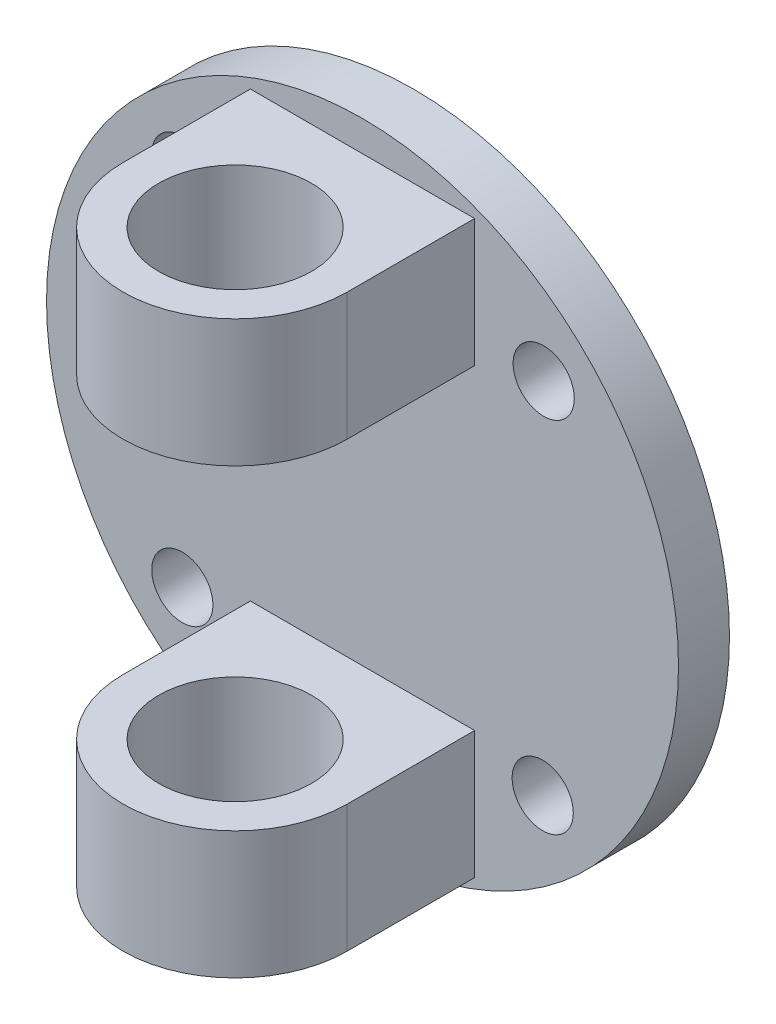
SolidWorks part; units mm, degrees
ref_plane "Front Plane" through (0, 0, 0) normal (0, 0, 1) x (1, 0, 0)
ref_plane "Top Plane" through (0, 0, 0) normal (0, 1, 0) x (1, 0, 0)
ref_plane "Right Plane" through (0, 0, 0) normal (1, 0, 0) x (0, 0, -1)
sketch "Sketch1" plane through (0, 0, 0) normal (0, 0, 1) x (1, 0, 0)
  circle A0 centre (0, 0) radius 62
  dimension "D1" = 124
extrude "Boss-Extrude1" add sketch "Sketch1" along normal blind 10 contours A0
sketch "Sketch2" plane through (0, 0, 10) normal (0, 0, 1) x (1, 0, 0)
  circle A2 centre (35.3553, -35.3553) radius 6
  circle A3 centre (-35.3553, -35.3553) radius 6
  circle A4 centre (-35.3553, 35.3553) radius 6
  circle A5 centre (35.5489, 35.1607) radius 6
  dimension "D1" = 12
  dimension "D2" = 12
  dimension "D3" = 12
  dimension "D4" = 12
extrude "Cut-Extrude1" cut sketch "Sketch2" against normal blind 10
sketch "Sketch4" plane through (0, 0, 10) normal (0, 0, 1) x (1, 0, 0)
  line L4 (-22, 31) -> (-22, 56)
  line L7 (22, 31) -> (22, 56)
  line L8 (22, 56) -> (-22, 56)
  line L10 (22, -31) -> (-22, -31)
  line L11 (-22, -31) -> (-22, -56)
  line L12 (-22, -56) -> (22, -56)
  line L13 (22, -56) -> (22, -31)
  line L14 (-22, 31) -> (22, 31)
  dimension "D1" = 25
  dimension "D2" = 25
  dimension "D4" = 25
  dimension "D5" = 44
extrude "Boss-Extrude2" add sketch "Sketch4" along normal blind 25
sketch "Sketch5" plane through (0, 56, 0) normal (0, 1, 0) x (1, 0, 0)
  line L0 (22, -35) -> (-22, -35) construction
  line L1 (-22, -35) -> (22, -35)
  arc A0 (-22, -35) -> (22, -35) centre (0, -35) ccw
  dimension "D1" = 44
extrude "Boss-Extrude5" add sketch "Sketch5" against normal blind 25 contours A0 L1
sketch "Sketch8" plane through (0, -56, 0) normal (0, -1, 0) x (1, 0, 0)
  line L0 (-22, 35) -> (22, 35) construction
  line L1 (-22, 35) -> (22, 35)
  arc A0 (22, 35) -> (-22, 35) centre (0, 35) ccw
extrude "Boss-Extrude6" add sketch "Sketch8" against normal blind 25
sketch "Sketch9" plane through (0, 56, 0) normal (0, 1, 0) x (1, 0, 0)
  circle A1 centre (0, -35) radius 15
  dimension "D1" = 30
extrude "Cut-Extrude2" cut sketch "Sketch9" against normal blind 25
sketch "Sketch10" plane through (0, -56, 0) normal (0, -1, 0) x (1, 0, 0)
  circle A0 centre (0, 35) radius 15
  dimension "D1" = 30
extrude "Cut-Extrude3" cut sketch "Sketch10" against normal blind 25
